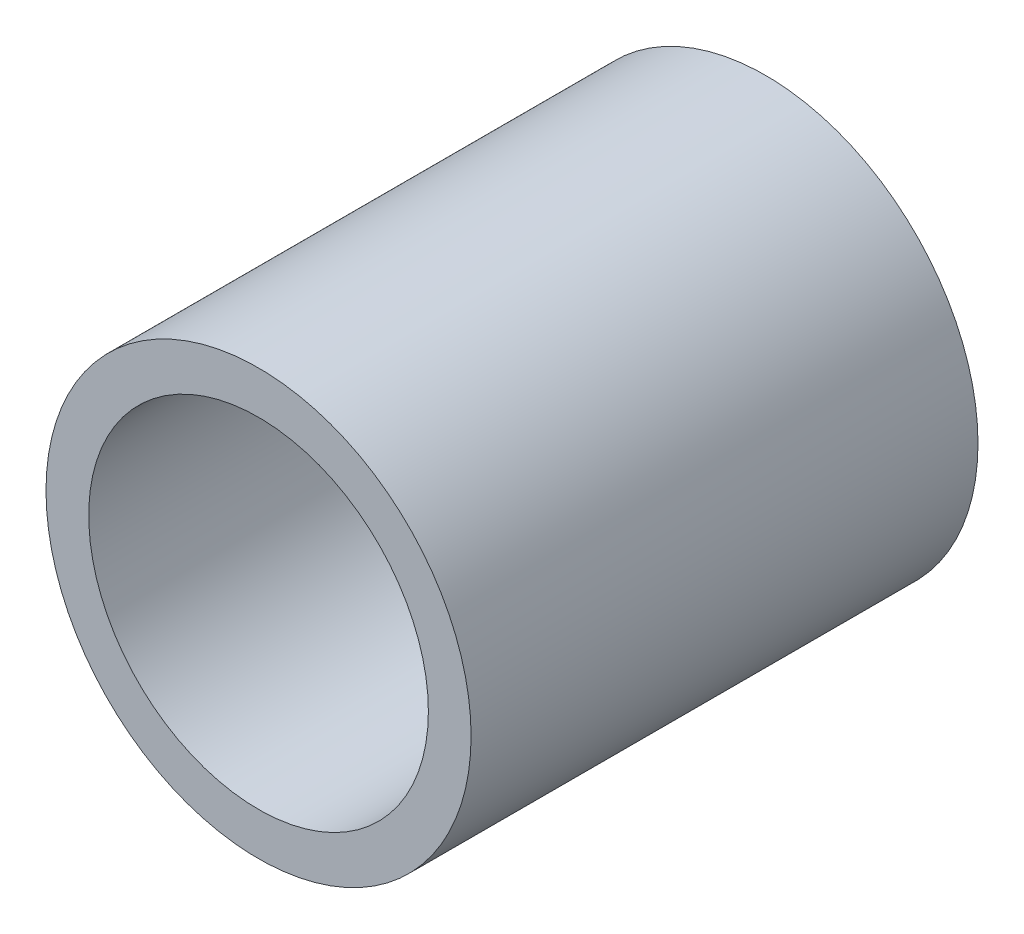
SolidWorks part; units mm, degrees
material "PVC Rígido"
ref_plane "Alzado" through (0, 0, 0) normal (0, 0, 1) x (1, 0, 0)
ref_plane "Planta" through (0, 0, 0) normal (0, 1, 0) x (1, 0, 0)
ref_plane "Vista lateral" through (0, 0, 0) normal (1, 0, 0) x (0, 0, -1)
sketch "Croquis1" plane through (0, 0, 0) normal (0, 0, 1) x (1, 0, 0)
  circle A0 centre (0, 0) radius 8.51
  circle A1 centre (0, 0) radius 10.65
  dimension "D1" = 17.02
  dimension "D2" = 21.3
extrude "Saliente-Extruir1" add sketch "Croquis1" along normal blind 25.4
